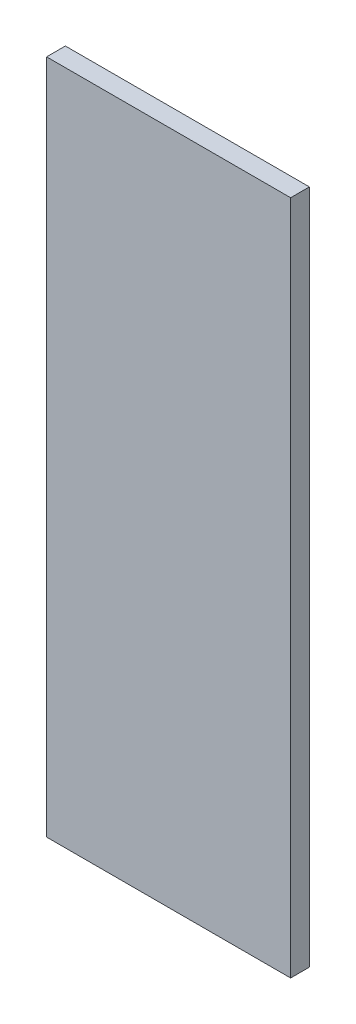
SolidWorks part; units mm, degrees
ref_plane "Front Plane" through (0, 0, 0) normal (0, 0, 1) x (1, 0, 0)
ref_plane "Top Plane" through (0, 0, 0) normal (0, 1, 0) x (1, 0, 0)
ref_plane "Right Plane" through (0, 0, 0) normal (1, 0, 0) x (0, 0, -1)
sketch "Sketch1" plane through (0, 0, 0) normal (0, 0, 1) x (1, 0, 0)
  line L1 (-309.6408, 187.083) -> (-144.5408, 187.083)
  line L2 (-309.6408, 187.083) -> (-309.6408, -270.117)
  line L3 (-309.6408, -270.117) -> (-144.5408, -270.117)
  line L4 (-144.5408, 187.083) -> (-144.5408, -270.117)
  dimension "D1" = 457.2
  dimension "D2" = 165.1
extrude "Boss-Extrude1" add sketch "Sketch1" along normal blind 12.7
